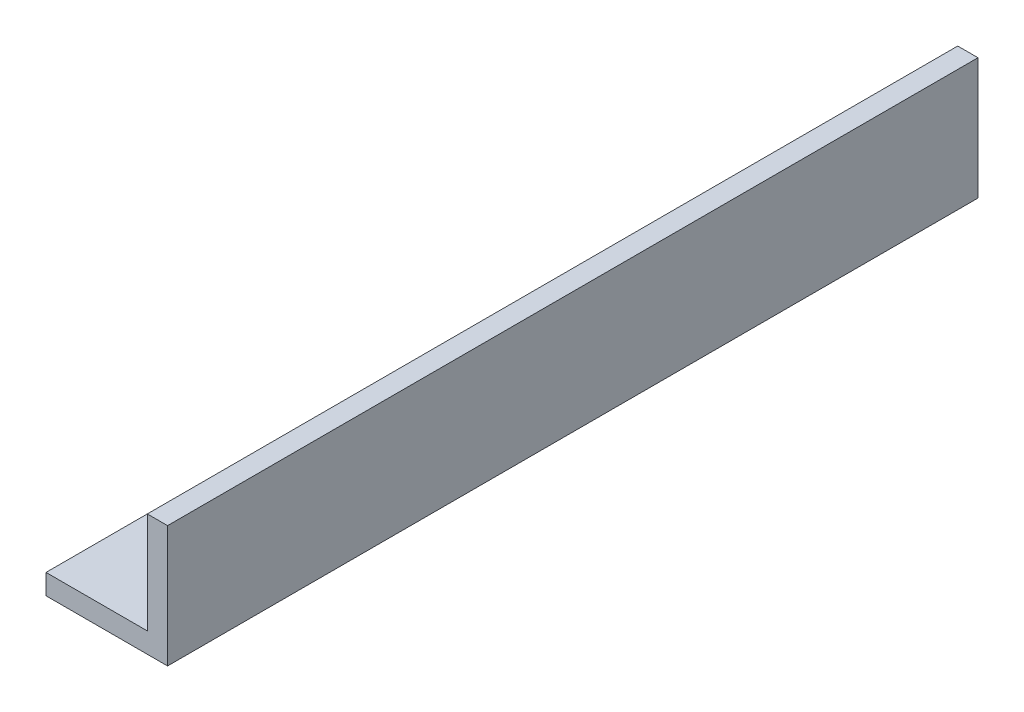
SolidWorks part; units mm, degrees
ref_plane "Front Plane" through (0, 0, 0) normal (0, 0, 1) x (1, 0, 0)
ref_plane "Top Plane" through (0, 0, 0) normal (0, 1, 0) x (1, 0, 0)
ref_plane "Right Plane" through (0, 0, 0) normal (1, 0, 0) x (0, 0, -1)
sketch "Sketch1" plane through (0, 0, 0) normal (0, 0, 1) x (1, 0, 0)
  line L0 (0, 0) -> (19.05, 0)
  line L1 (19.05, 0) -> (19.05, 19.05)
  dimension "D1" = 19.05
  dimension "D2" = 19.05
extrude "Extrude-Thin1" add sketch "Sketch1" along normal blind 127 thin thin type one direction reverse wall 3.175
